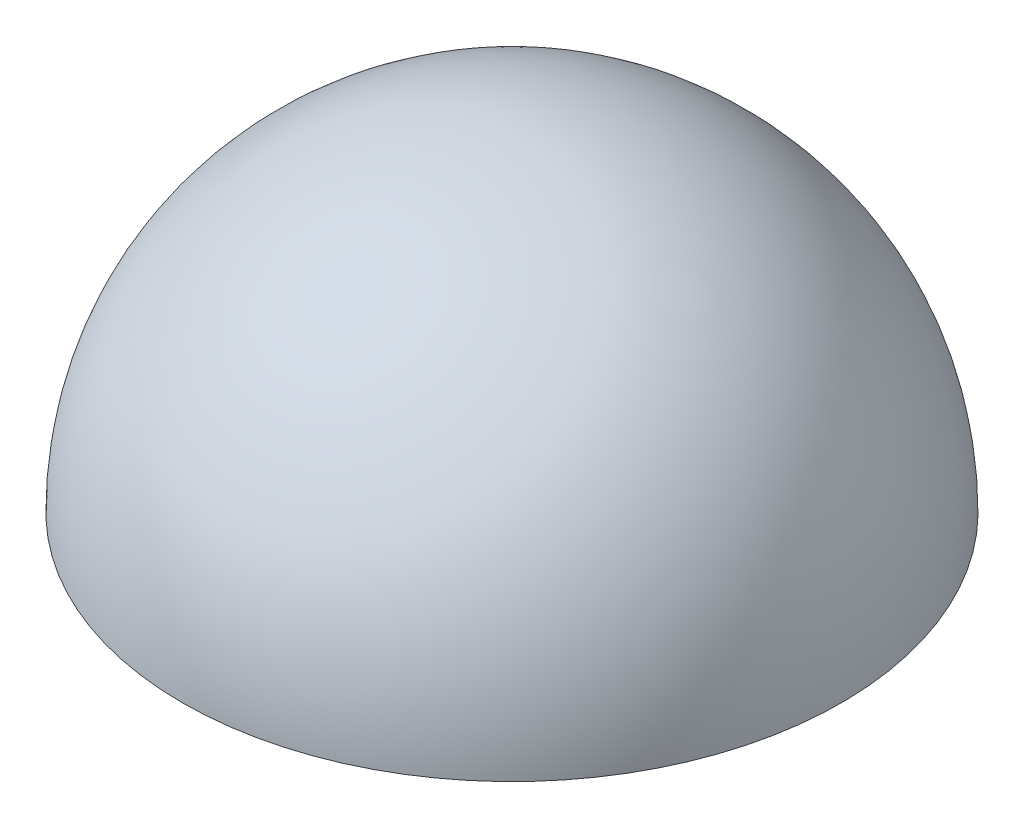
SolidWorks part; units mm, degrees
material "Glass"
ref_plane "Front Plane" through (0, 0, 0) normal (0, 0, 1) x (1, 0, 0)
ref_plane "Top Plane" through (0, 0, 0) normal (0, 1, 0) x (1, 0, 0)
ref_plane "Right Plane" through (0, 0, 0) normal (1, 0, 0) x (0, 0, -1)
sketch "Sketch1" plane through (0, 0, 0) normal (0, 1, 0) x (1, 0, 0)
  line L0 (-23.903, -1.9393) -> (26.897, -1.9613)
  arc A0 (-23.903, -1.9393) -> (26.897, -1.9613) centre (1.497, -1.9503) cw
revolve "Revolve1" add sketch "Sketch1" angle 180 about L0
shell "Shell1" thickness 1.27
